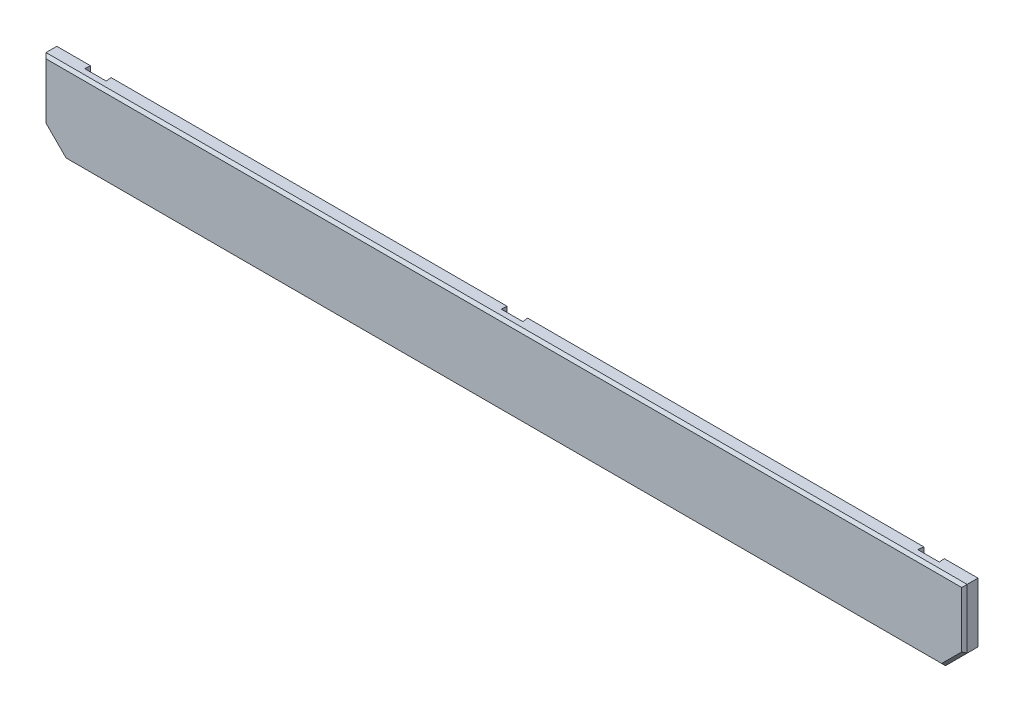
SolidWorks part; units mm, degrees
ref_plane "Plan de face" through (0, 0, 0) normal (0, 0, 1) x (1, 0, 0)
ref_plane "Plan de dessus" through (0, 0, 0) normal (0, 1, 0) x (1, 0, 0)
ref_plane "Plan de droite" through (0, 0, 0) normal (1, 0, 0) x (0, 0, -1)
sketch "Esquisse1" plane through (0, 0, 0) normal (0, 0, 1) x (1, 0, 0)
  line L1 (0, 0) -> (1700, 0)
  line L2 (0, 0) -> (0, 150)
  line L3 (0, 150) -> (1700, 150)
  line L4 (1700, 0) -> (1700, 150)
  dimension "D1" = 1700
  dimension "D2" = 150
extrude "Boss.-Extru.1" add sketch "Esquisse1" along normal blind 25
sketch "Esquisse2" plane through (0, 150, 0) normal (0, 1, 0) x (1, 0, 0)
  line L0 (100, 0) -> (101.2278, -10)
  line L1 (1700, 0) -> (0, 0) construction
  line L2 (101.2278, -10) -> (61.2278, -10)
  line L3 (81.2278, -10) -> (81.2278, 0) construction
  line L4 (850, -25) -> (850, 0) construction
  line L5 (1700, -25) -> (0, -25) construction
  line L6 (62.4557, 0) -> (61.2278, -10)
  line L7 (62.4557, 0) -> (100, 0)
  line L8 (1618.7722, -10) -> (1618.7722, 0) construction
  line L9 (1637.5443, 0) -> (1638.7722, -10)
  line L10 (1598.7722, -10) -> (1638.7722, -10)
  line L11 (1600, 0) -> (1598.7722, -10)
  line L12 (1637.5443, 0) -> (1600, 0)
  line L13 (465.6139, -25) -> (465.6139, 0) construction
  line L14 (850, -10) -> (850, 0) construction
  line L15 (868.7722, 0) -> (831.2278, 0)
  line L16 (868.7722, 0) -> (870, -10)
  line L17 (830, -10) -> (870, -10)
  line L18 (831.2278, 0) -> (830, -10)
  line L19 (101.2278, -10) -> (101.2278, 0) construction
  dimension "D1" = 40
  dimension "D2" = 10
  dimension "D3" = 7
  dimension "D4" = 750
extrude "Enlèv. mat.-Extru.1" cut sketch "Esquisse2" against normal through all both and the other way through all
chamfer "Chanfrein1" [suppressed] distance 40 angle 45
chamfer "Chanfrein2" distance 40 angle 45 2 edges at (0, 0, 12.5) (1700, 0, 12.5)
chamfer "Chanfrein3" distance 5 angle 45 6 edges at (850, 150, 25) (1700, 95, 25) (1680, 20, 25) (850, 0, 25) (20, 20, 25) (0, 95, 25)
